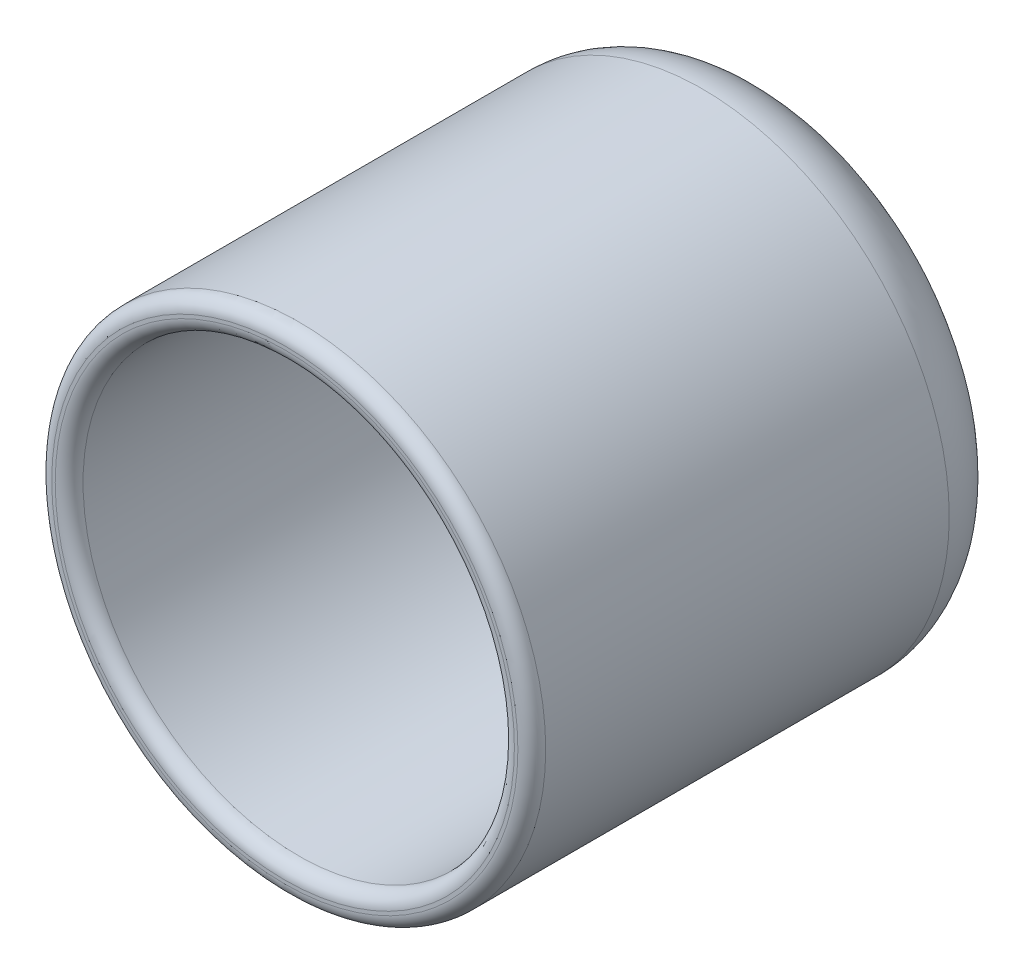
SolidWorks part; units mm, degrees
ref_plane "Front Plane" through (0, 0, 0) normal (0, 0, 1) x (1, 0, 0)
ref_plane "Top Plane" through (0, 0, 0) normal (0, 1, 0) x (1, 0, 0)
ref_plane "Right Plane" through (0, 0, 0) normal (1, 0, 0) x (0, 0, -1)
sketch "Sketch1" plane through (0, 0, 0) normal (0, 0, 1) x (1, 0, 0)
  circle A0 centre (0, 0) radius 3.55
  dimension "D1" = 7.1
extrude "Boss-Extrude1" add sketch "Sketch1" along normal blind 7
sketch "Sketch2" plane through (0, 0, 7) normal (0, 0, 1) x (1, 0, 0)
  circle A0 centre (0, 0) radius 3.1
  circle A1 centre (0, 0) radius 3.55 construction
  dimension "D1" = 6.2
  dimension "D2" = 0.45
extrude "Cut-Extrude1" cut sketch "Sketch2" against normal blind 6.5
fillet "Fillet1" radius 0.2 2 edges at (3.1, 0, 7) (3.55, 0, 7)
fillet "Fillet2" radius 1 1 edges at (3.55, 0, 0)
